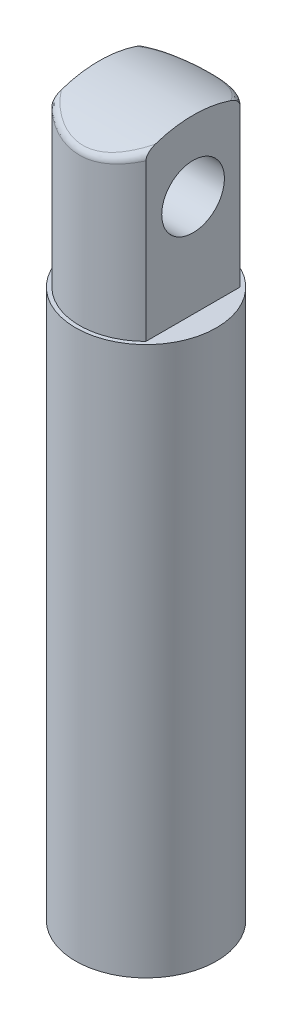
SolidWorks part; units mm, degrees
material "1350 合金"
ref_plane "前视基准面" through (0, 0, 0) normal (0, 0, 1) x (1, 0, 0)
ref_plane "上视基准面" through (0, 0, 0) normal (0, 1, 0) x (1, 0, 0)
ref_plane "右视基准面" through (0, 0, 0) normal (1, 0, 0) x (0, 0, -1)
sketch "草图1" plane through (0, 0, 0) normal (0, 1, 0) x (1, 0, 0)
  circle A0 centre (0, 0) radius 4.5
  dimension "D1" = 9
extrude "凸台-拉伸1" add sketch "草图1" along normal blind 55
sketch "草图2" plane through (0, 55, 0) normal (0, 1, 0) x (1, 0, 0)
  line L0 (0, 4.25) -> (0, -5.0818) construction
  line L1 (-3, 3.0104) -> (-3, -3.0104)
  line L2 (3, 3.0104) -> (3, -3.0104)
  line L4 (-3, 4.8439) -> (-3, -5.0818) construction
  line L5 (0, 4.8439) -> (0, -5.0818) construction
  line L6 (3, 4.8439) -> (3, -5.0818) construction
  arc A0 (-3, -3.0104) -> (3, -3.0104) centre (0, 0) ccw
  arc A1 (3, 3.0104) -> (-3, 3.0104) centre (0, 0) ccw
  dimension "D1" = 8.5
  dimension "D2" = 3
  dimension "D3" = 3
extrude "凸台-拉伸2" add sketch "草图2" along normal blind 15
sketch "草图4" plane through (-3, 0, 0) normal (-1, 0, 0) x (0, 0, 1)
  line L0 (0, 55) -> (0, 61.5) construction
  line L1 (4.5, 55) -> (-4.5, 55) construction
  circle A0 centre (0, 61.5) radius 2
  dimension "D2" = 4
  dimension "D1" = 6.5
extrude "切除-拉伸1" cut sketch "草图4" against normal through all
sketch "草图5" plane through (-3, 0, 0) normal (-1, 0, 0) x (0, 0, 1)
  line L0 (0, 61.5) -> (0, 58.5) construction
  line L1 (-4.8133, 64.2517) -> (-4.8133, 72.4064)
  line L2 (-4.8133, 72.4064) -> (5.4669, 72.4064)
  line L3 (5.4669, 72.4064) -> (5.4669, 63.6345)
  arc A1 (5.4669, 63.6345) -> (-4.8133, 64.2517) centre (0, 58.5) ccw
  dimension "D1" = 3
  dimension "D2" = 15
extrude "切除-拉伸3" cut sketch "草图5" against normal through all
fillet "圆角1" radius 0.5 2 edges at (-0.4387, 64.6952, -4.2273) (0.4387, 64.6952, 4.2273)
sketch "Sketch1" plane through (0, 0, 0) normal (0, -1, 0) x (1, 0, 0)
  circle A0 centre (0, 0) radius 4.5
  dimension "D1" = 9
extrude "Cut-Extrude1" cut sketch "Sketch1" against normal blind 20
